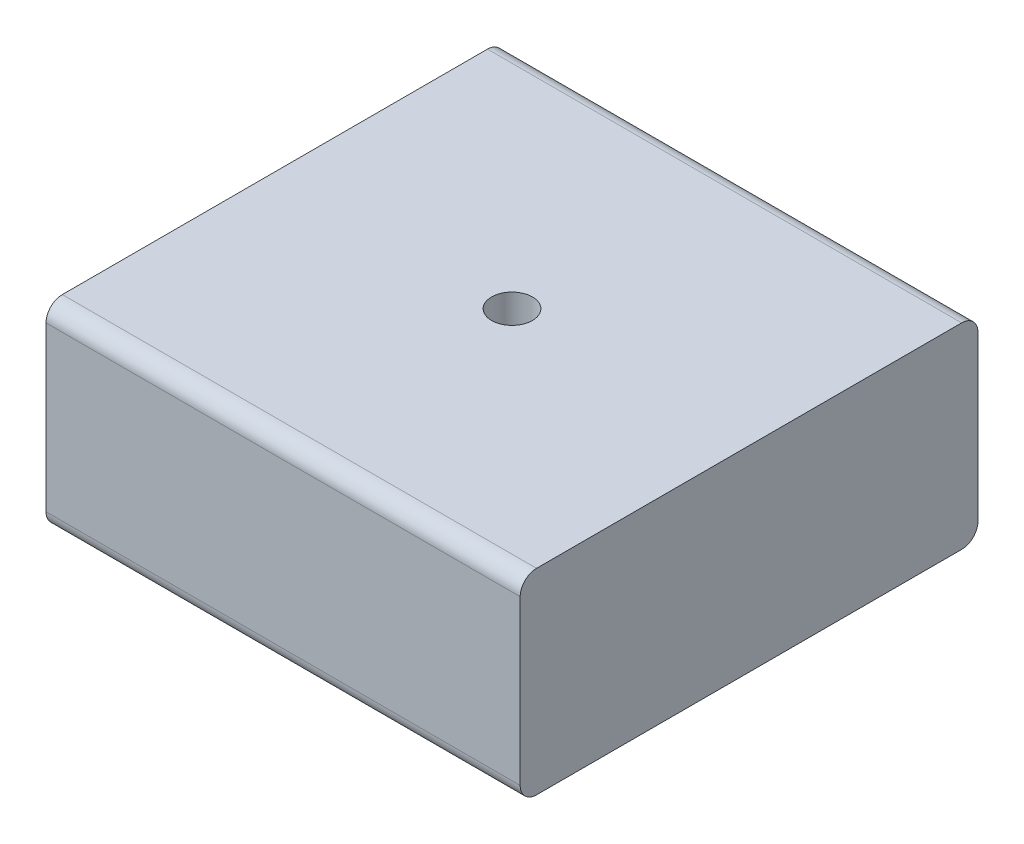
SolidWorks part; units mm, degrees
material "Pine"
ref_plane "Front Plane" through (0, 0, 0) normal (0, 0, 1) x (1, 0, 0)
ref_plane "Top Plane" through (0, 0, 0) normal (0, 1, 0) x (1, 0, 0)
ref_plane "Right Plane" through (0, 0, 0) normal (1, 0, 0) x (0, 0, -1)
sketch "Sketch1" plane through (0, 0, 0) normal (0, 0, 1) x (1, 0, 0)
  line L1 (-46.0375, 38.1) -> (46.0375, 38.1)
  line L2 (-46.0375, 38.1) -> (-46.0375, 0)
  line L3 (-46.0375, 0) -> (46.0375, 0)
  line L4 (46.0375, 38.1) -> (46.0375, 0)
  point P4 (0, 0)
  dimension "D1" = 92.075
  dimension "D2" = 38.1
extrude "Boss-Extrude1" add sketch "Sketch1" along normal blind 88.9
fillet "Fillet1" radius 3.175 4 edges at (0, 0, 0) (0, 0, 88.9) (0, 38.1, 0) (0, 38.1, 88.9)
sketch "Sketch2" plane through (0, 38.1, 0) normal (0, 1, 0) x (1, 0, 0)
  line L0 (-46.0375, -85.725) -> (-46.0375, -3.175) construction
  point P0 (0, -44.45)
  point P1 (0, 0)
  point P2 (0, 0)
  point P5 (-46.0375, -44.45)
hole_wizard "5/16 (0.3125) Diameter Hole1" positions "Sketch3" profile "Sketch4" hole size "5/16" standard "ANSI Inch" end condition up to next
sketch "Sketch3" plane through (0, 38.1, 0) normal (0, 1, 0) x (1, 0, 0)
  point P0 (0, -44.45)
sketch "Sketch4" plane through (0, 38.1, 44.45) normal (1, 0, 0) x (0, 0, 1)
  line L0 (0, 0) -> (0, 38.1)
  line L1 (0, 38.1) -> (3.9687, 38.1)
  line L2 (3.9687, 38.1) -> (3.9687, 0)
  line L5 (3.9687, 0) -> (0, 0)
  line L11 (0, -6.35) -> (0, 107.95) construction
  dimension "Thru Hole Dia." = 7.9375
  dimension "Thru Hole Depth" = 38.1
